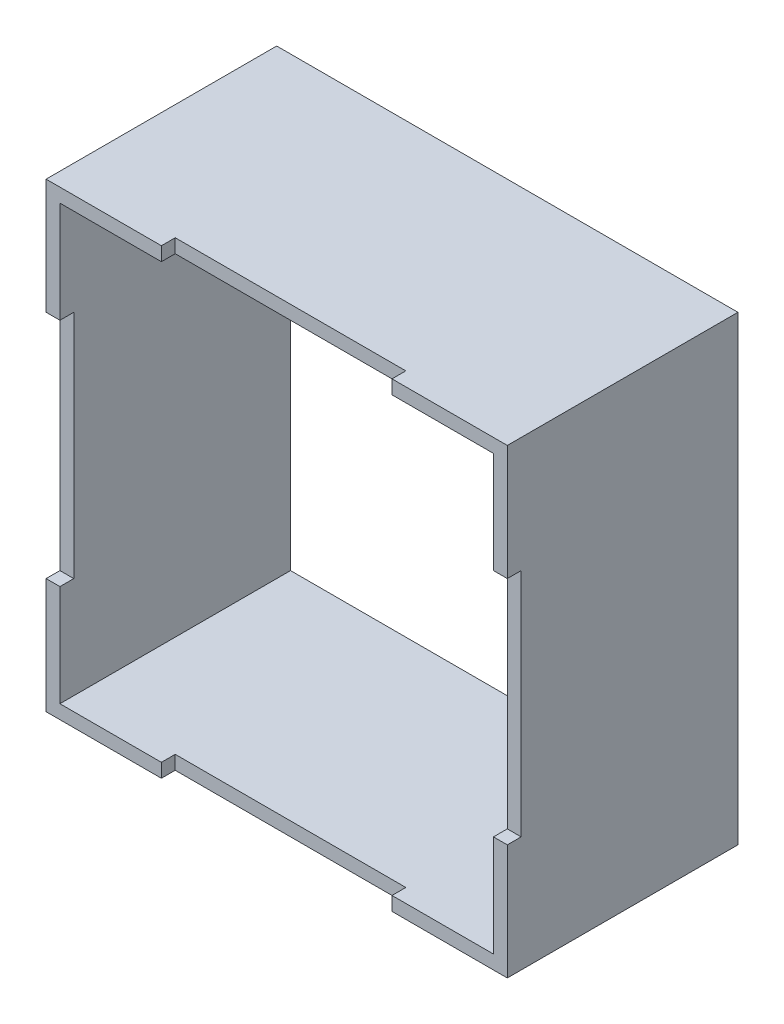
SolidWorks part; units mm, degrees
ref_plane "前视基准面" through (0, 0, 0) normal (0, 0, 1) x (1, 0, 0)
ref_plane "上视基准面" through (0, 0, 0) normal (0, 1, 0) x (1, 0, 0)
ref_plane "右视基准面" through (0, 0, 0) normal (1, 0, 0) x (0, 0, -1)
sketch "草图1" plane through (0, 0, 0) normal (0, 0, 1) x (1, 0, 0)
  line L1 (0, 0) -> (100, 0)
  line L2 (0, 0) -> (0, -100)
  line L3 (0, -100) -> (100, -100)
  line L4 (100, 0) -> (100, -100)
  line L5 (3, -3) -> (97, -3)
  line L6 (3, -3) -> (3, -97)
  line L7 (3, -97) -> (97, -97)
  line L8 (97, -3) -> (97, -97)
  dimension "D1" = 100
  dimension "D2" = 100
  dimension "D3" = 3
  dimension "D4" = 3
  dimension "D5" = 3
  dimension "D6" = 3
extrude "凸台-拉伸1" add sketch "草图1" along normal blind 50
sketch "草图2" plane through (0, 0, 0) normal (-1, 0, 0) x (0, 0, 1)
  line L0 (0, -50) -> (50, -50) construction
  line L1 (0, 0) -> (0, -100) construction
  line L2 (50, 0) -> (50, -100) construction
  line L3 (50, -25) -> (50, -75)
  line L4 (50, -75) -> (47, -75)
  line L5 (47, -75) -> (47, -25)
  line L6 (47, -25) -> (50, -25)
  dimension "D1" = 50
  dimension "D2" = 3
  dimension "D3" = 25
extrude "切除-拉伸1" cut sketch "草图2" against normal through all
sketch "草图3" plane through (0, -100, 0) normal (0, -1, 0) x (1, 0, 0)
  line L0 (50, 50) -> (50, 0) construction
  line L1 (0, 50) -> (100, 50) construction
  line L2 (0, 0) -> (100, 0) construction
  line L3 (25, 50) -> (75, 50)
  line L4 (75, 50) -> (75, 47)
  line L5 (75, 47) -> (25, 47)
  line L6 (25, 47) -> (25, 50)
  dimension "D1" = 50
  dimension "D2" = 25
  dimension "D3" = 3
extrude "切除-拉伸2" cut sketch "草图3" against normal through all
